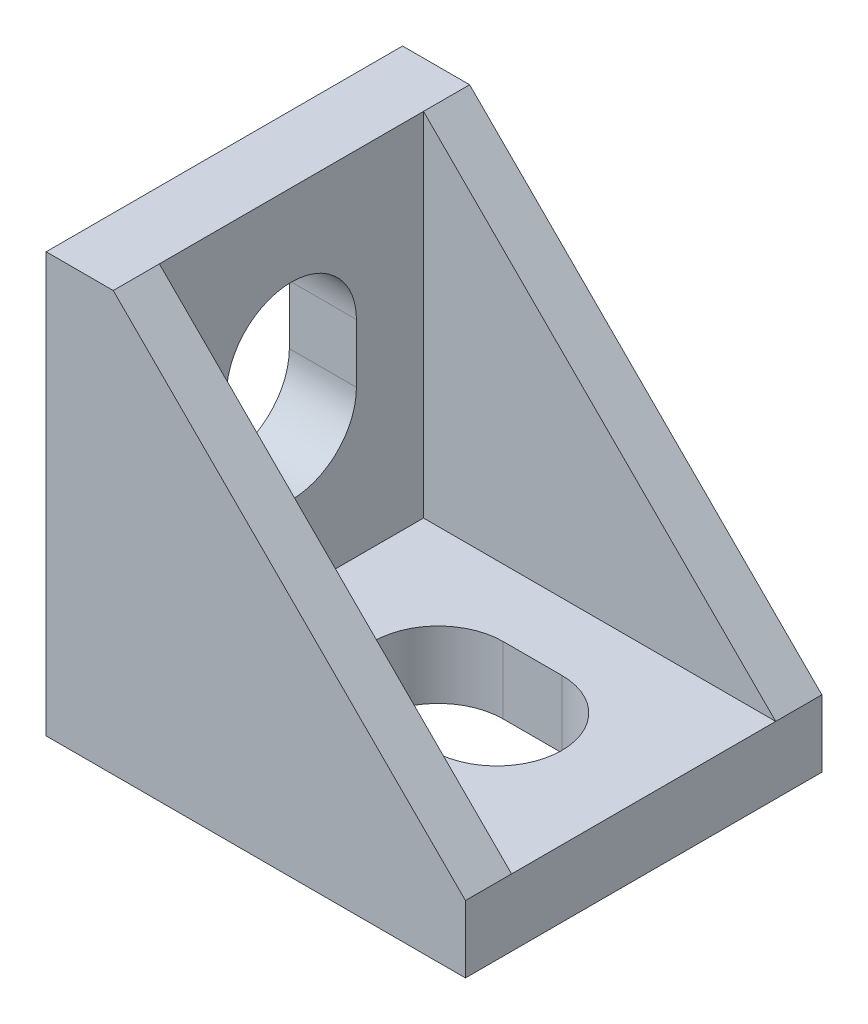
SolidWorks part; units mm, degrees
ref_plane "前视基准面" through (0, 0, 0) normal (0, 0, 1) x (1, 0, 0)
ref_plane "上视基准面" through (0, 0, 0) normal (0, 1, 0) x (1, 0, 0)
ref_plane "右视基准面" through (0, 0, 0) normal (1, 0, 0) x (0, 0, -1)
sketch "草图1" plane through (0, 0, 0) normal (0, 0, 1) x (1, 0, 0)
  line L1 (-10, -10) -> (10, -10)
  line L2 (-10, -10) -> (-10, 10)
  line L3 (-10, 10) -> (10, 10)
  line L4 (10, -10) -> (10, 10)
  line L5 (0, 10) -> (0, -10) construction
  line L6 (-10, 0) -> (10, 0) construction
  point P0 (0, 0)
extrude "凸台-拉伸1" add sketch "草图1" along normal blind 17
sketch "草图2" plane through (0, 10, 0) normal (0, 1, 0) x (1, 0, 0)
  line L0 (10, 0) -> (10, -2.2)
  line L1 (10, -17) -> (10, 0) construction
  line L2 (10, -17) -> (10, -14.8)
  line L3 (10, -14.8) -> (-6.8, -14.8)
  line L4 (-6.8, -14.8) -> (-6.8, -2.2)
  line L5 (-6.8, -2.2) -> (10, -2.2)
  line L6 (10, -14.8) -> (10, -2.2)
  line M5 (10, -17) -> (10, 0)
extrude "切除-拉伸1" cut sketch "草图2" against normal blind 16.8 contours L5 L4 L3 M5
sketch "草图3" plane through (0, 0, 2.2) normal (0, 0, 1) x (1, 0, 0)
  line L0 (-6.8, 10) -> (10, -6.8)
  line L1 (10, -6.8) -> (10, 10)
  line L2 (10, 10) -> (-6.8, 10)
extrude "切除-拉伸2" cut sketch "草图3" against normal blind 16.8 and the other way blind 16.8
sketch "草图4" plane through (-6.8, 0, 0) normal (1, 0, 0) x (0, 0, -1)
  line L3 (-5.4, 0.2) -> (-5.4, 3)
  line L5 (-11.6, 0.2) -> (-11.6, 3)
  arc A0 (-11.6, 0.2) -> (-5.4, 0.2) centre (-8.5, 0.2) ccw
  arc A1 (-11.6, 3) -> (-5.4, 3) centre (-8.5, 3) cw
extrude "切除-拉伸3" cut sketch "草图4" against normal blind 16.8
ref_point "点1"
ref_plane "基准面4" through (0, 0, 0) normal (0.7071, -0.7071, 0) x (0, 0, -1)
mirror "镜向1" about plane through (0, 0, 0) normal (0.7071, -0.7071, 0) of "切除-拉伸3"
